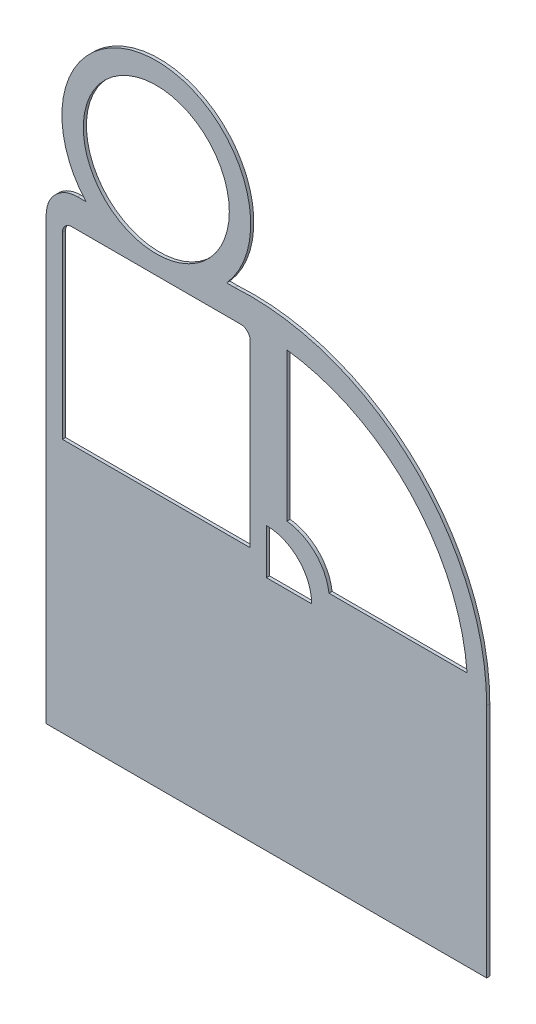
SolidWorks part; units mm, degrees
ref_plane "Front Plane" through (0, 0, 0) normal (0, 0, 1) x (1, 0, 0)
ref_plane "Top Plane" through (0, 0, 0) normal (0, 1, 0) x (1, 0, 0)
ref_plane "Right Plane" through (0, 0, 0) normal (1, 0, 0) x (0, 0, -1)
sketch "Sketch1" plane through (0, 0, 0) normal (0, 0, 1) x (1, 0, 0)
  line L0 (820.1756, -512.1087) -> (846.5688, -512.1087)
  line L1 (346.5688, -512.1087) -> (372.962, -512.1087)
  line L2 (246.5688, -612.1087) -> (246.5688, -2012.2429)
  line L3 (246.5688, -2012.2429) -> (946.5688, -2012.2429)
  line L4 (946.5688, -612.1087) -> (946.5688, -1262.2429)
  line L5 (1090.1781, -1260.4164) -> (946.5688, -1260.4164)
  line L6 (246.5688, -1812.1087) -> (1646.5688, -1812.1087) construction
  line L7 (1646.5688, -1262.2429) -> (246.5688, -1262.2429) construction
  line L8 (946.5688, -2012.2429) -> (1646.5688, -2012.2429)
  line L11 (1646.5688, -2012.2429) -> (1646.5688, -1262.2429)
  line L12 (246.5688, -2012.2429) -> (1646.5688, -2012.2429)
  line L13 (246.5688, -2012.2429) -> (246.5688, -1812.1087)
  line L15 (1646.5688, -2012.2429) -> (1646.5688, -1812.1087)
  line L17 (946.5688, -1262.2429) -> (946.5688, -1260.4164)
  line L18 (946.5688, -1262.2429) -> (946.5688, -2012.2429) construction
  line L19 (246.5688, -1262.2429) -> (301.2022, -1203.7142) construction
  line L20 (1012.065, -600.8625) -> (1012.065, -1072.0687)
  line L21 (328.2572, -603.7142) -> (864.8804, -603.7142)
  line L22 (298.2572, -633.7142) -> (298.2572, -1203.7142)
  line L23 (298.2572, -1203.7142) -> (894.8804, -1203.7142)
  line L24 (894.8804, -633.7142) -> (894.8804, -1203.7142)
  line L25 (1145.3782, -1203.7142) -> (1584.2631, -1203.7142)
  arc A0 (820.1756, -512.1087) -> (372.962, -512.1087) centre (596.5688, -312.1087) ccw
  arc A1 (346.5688, -512.1087) -> (246.5688, -612.1087) centre (346.5688, -612.1087) ccw
  arc A2 (846.5688, -512.1087) -> (946.5688, -612.1087) centre (846.5688, -612.1087) cw
  arc A3 (846.5688, -512.1087) -> (1646.5688, -1262.2429) centre (894.8804, -1262.2429) cw
  arc A4 (1090.1781, -1260.4164) -> (946.5688, -1116.8072) centre (946.5688, -1260.4164) ccw
  arc A5 (328.2572, -603.7142) -> (298.2572, -633.7142) centre (328.2572, -633.7142) ccw
  arc A6 (864.8804, -603.7142) -> (894.8804, -633.7142) centre (864.8804, -633.7142) cw
  circle A7 centre (596.5688, -312.1087) radius 232.0124
  arc A8 (1012.065, -600.8625) -> (1584.2631, -1203.7142) centre (927.8379, -1253.7842) cw
  arc A9 (1012.065, -1072.0687) -> (1145.3782, -1203.7142) centre (994.8447, -1222.8309) cw
  point P0 (596.4549, -1260.4164)
  point P6 (596.5688, -887.2884)
  dimension "D1" = 1400
  dimension "D2" = 570
extrude "Boss-Extrude2" add sketch "Sketch1" against normal blind 10
